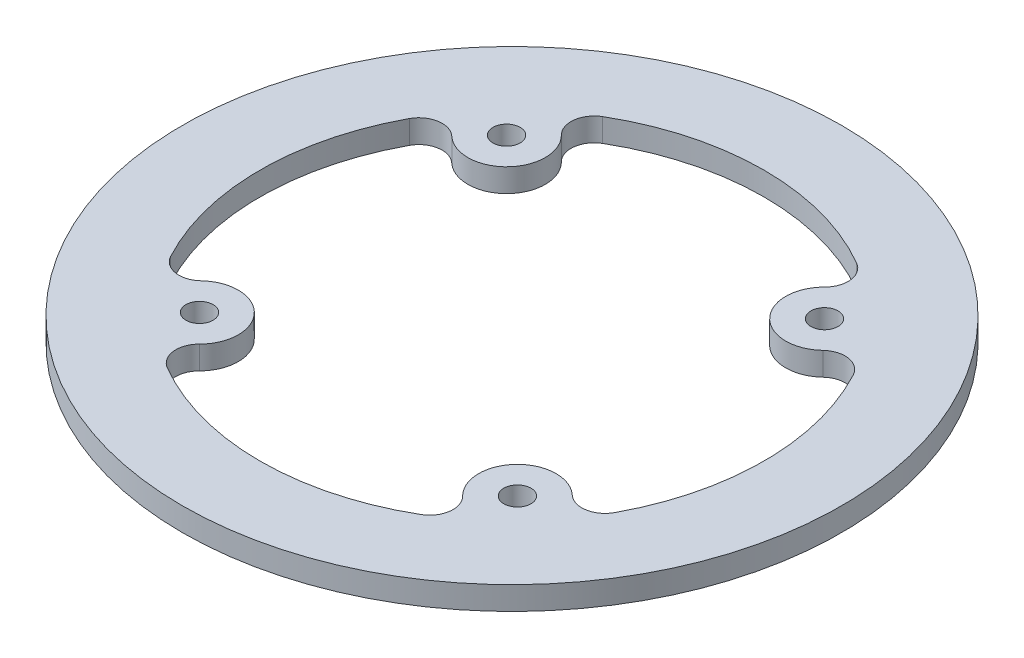
SolidWorks part; units mm, degrees
ref_plane "正面" through (0, 0, 0) normal (0, 0, 1) x (1, 0, 0)
ref_plane "平面" through (0, 0, 0) normal (0, 1, 0) x (1, 0, 0)
ref_plane "右側面" through (0, 0, 0) normal (1, 0, 0) x (0, 0, -1)
sketch "ｽｹｯﾁ1" plane through (0, 0, 0) normal (0, 1, 0) x (1, 0, 0)
  line L0 (0, 0) -> (0, 28.5) construction
  line L1 (0, 0) -> (45, 0) construction
  line L2 (-12, -29) -> (12, -29) construction
  line L3 (-12, -29) -> (-12, 29) construction
  line L4 (-12, 29) -> (12, 29) construction
  line L5 (12, -29) -> (12, 29) construction
  line L6 (-12, -29) -> (12, 29) construction
  line L7 (-12, 29) -> (12, -29) construction
  circle A0 centre (0, 0) radius 28.5 construction
  circle A5 centre (0, 0) radius 45
  circle A7 centre (-20.5, -19.799) radius 6.5 construction
  circle A8 centre (-20.5, -19.799) radius 2
  circle A9 centre (20.5, -19.799) radius 2
  circle A10 centre (20.5, 19.799) radius 2
  circle A11 centre (-20.5, 19.799) radius 2
  dimension "D1" = 57
  dimension "D2" = 58
  dimension "D3" = 24
  dimension "D5" = 90
  dimension "D6" = 8.5
  dimension "D4" = 13
  dimension "D7" = 4
extrude "ﾎﾞｽ - 押し出し1" add sketch "ｽｹｯﾁ1" along normal blind 3
sketch "ｽｹｯﾁ2" plane through (0, 3, 0) normal (0, 1, 0) x (1, 0, 0)
  circle A0 centre (0, 0) radius 32.5
  circle A1 centre (-20.5, -19.799) radius 2 construction
  circle A3 centre (20.5, -19.799) radius 2 construction
  circle A5 centre (20.5, 19.799) radius 2 construction
  circle A7 centre (-20.5, 19.799) radius 2 construction
  circle A9 centre (-20.5, 19.799) radius 5
  circle A13 centre (-20.5, -19.799) radius 2
  circle A14 centre (20.5, -19.799) radius 2
  circle A15 centre (20.5, 19.799) radius 2
  circle A16 centre (-20.5, 19.799) radius 2
  circle A17 centre (-20.5, -19.799) radius 5
  circle A18 centre (20.5, -19.799) radius 5
  circle A19 centre (20.5, 19.799) radius 5
  dimension "D5" = 65
  dimension "D1" = 3
  dimension "D2" = 3
extrude "ｶｯﾄ - 押し出し1" cut sketch "ｽｹｯﾁ2" against normal through all contours A19 A0 A9 A17 A18
fillet "ﾌｨﾚｯﾄ1" radius 3 8 edges at (21.0408, 1.5, -24.7697) (25.4865, 1.5, -20.1666) (25.4865, 1.5, 20.1666) (21.0408, 1.5, 24.7697) (-21.0408, 1.5, 24.7697) (-25.4865, 1.5, 20.1666) (-25.4865, 1.5, -20.1666) (-21.0408, 1.5, -24.7697)
other "面の移動1" face at (0, 3, 45) parameters "D1"=2.5
other "面の移動2" face at (20.5, 3, -17.799) face at (-20.5, 3, -21.799) face at (-20.5, 3, 21.799) face at (20.5, 3, 17.799) parameters "D1"=0.15
other "面の移動3" face at (-20.5, 3, 21.949) face at (20.5, 3, 21.949) face at (20.5, 3, -17.649) face at (-20.5, 3, -17.649) parameters "D1"=0.4
